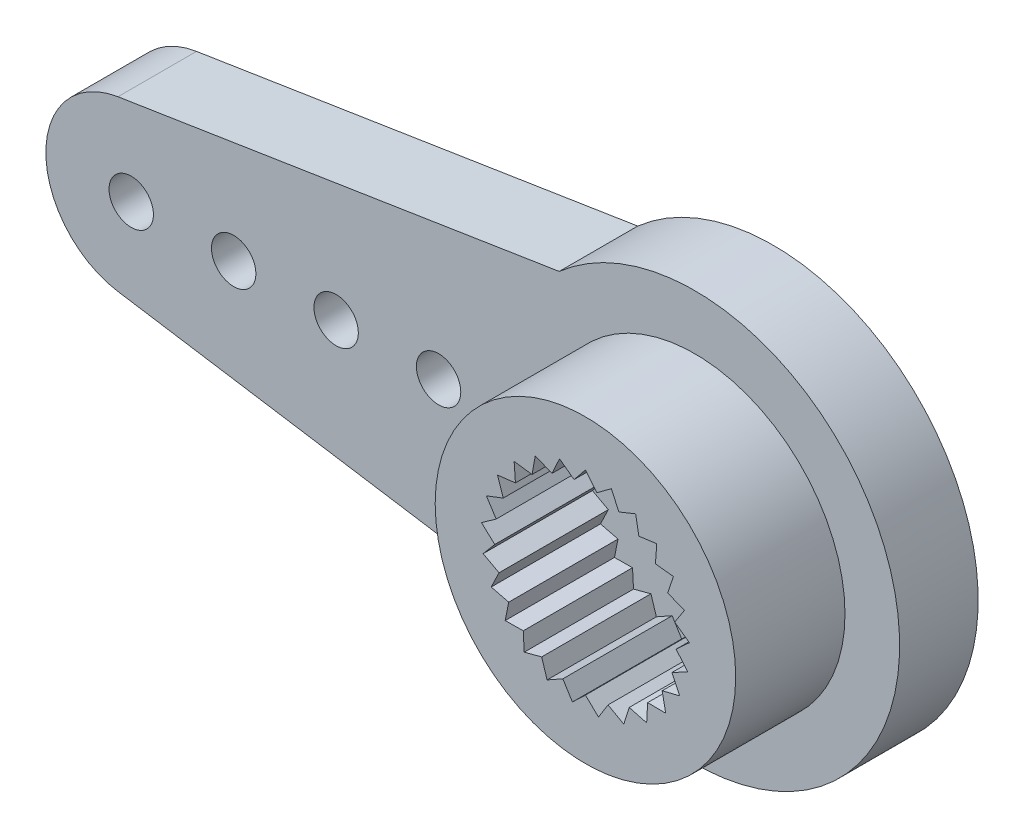
SolidWorks part; units mm, degrees
ref_plane "Front" through (0, 0, 0) normal (0, 0, 1) x (1, 0, 0)
ref_plane "Top" through (0, 0, 0) normal (0, 1, 0) x (1, 0, 0)
ref_plane "Right" through (0, 0, 0) normal (1, 0, 0) x (0, 0, -1)
sketch "Эскиз1" plane through (0, 0, 0) normal (0, 0, 1) x (1, 0, 0)
  line L0 (-3.9686, 4.5) -> (-16.8881, 2.4697)
  line L1 (-19, 4.5) -> (19, 4.5) construction
  line L2 (-19, 4.5) -> (-19, -4.5) construction
  line L3 (-19, -4.5) -> (19, -4.5) construction
  line L4 (19, 4.5) -> (19, -4.5) construction
  line L5 (0, -4.5) -> (0, 4.5) construction
  line L6 (-19, 0) -> (19, 0) construction
  line L7 (-3.9686, -4.5) -> (-16.8881, -2.4697)
  line L8 (3.9686, -4.5) -> (16.8881, -2.4697)
  line L9 (3.9686, 4.5) -> (16.8881, 2.4697)
  circle A0 centre (0, 0) radius 6 construction
  circle A1 centre (-16.5, 0) radius 2.5 construction
  arc A2 (-16.8881, 2.4697) -> (-16.8881, -2.4697) centre (-16.5, 0) ccw
  arc A3 (-3.9686, 4.5) -> (3.9686, 4.5) centre (0, 0) cw
  arc A4 (-3.9686, -4.5) -> (3.9686, -4.5) centre (0, 0) ccw
  circle A5 centre (16.5, 0) radius 2.5 construction
  arc A6 (16.8881, 2.4697) -> (16.8881, -2.4697) centre (16.5, 0) cw
  circle A7 centre (-16.5, 0) radius 0.65
  circle A8 centre (-13.5, 0) radius 0.65
  circle A9 centre (-10.5, 0) radius 0.65
  circle A10 centre (-7.5, 0) radius 0.65
  circle A11 centre (16.5, 0) radius 0.65
  circle A12 centre (7.5, 0) radius 0.65
  circle A13 centre (10.5, 0) radius 0.65
  circle A14 centre (13.5, 0) radius 0.65
  circle A15 centre (0, 0) radius 1.5
  dimension "D1" = 12
  dimension "D4" = 5
  dimension "D5" = 1.3
  dimension "D7" = 3
  dimension "D2" = 9
  dimension "D3" = 38
  dimension "D6" = 4
extrude "Бобышка-Вытянуть1" add sketch "Эскиз1" along normal blind 2.3
sketch "Эскиз2" plane through (0, 0, 2.3) normal (0, 0, 1) x (1, 0, 0)
  line L0 (0, 0) -> (0, 3.05) construction
  line L1 (0, 0) -> (0.3823, 3.0259) construction
  line L2 (0.3334, 2.6394) -> (0, 3.05)
  line L3 (-0.3334, 2.6394) -> (0, 3.05)
  line L4 (0.3334, 2.6394) -> (0.7585, 2.9542)
  line L5 (0.9794, 2.4736) -> (0.7585, 2.9542)
  line L6 (0.9794, 2.4736) -> (1.4693, 2.6727)
  line L7 (1.5638, 2.1523) -> (1.4693, 2.6727)
  line L8 (1.5638, 2.1523) -> (2.0879, 2.2234)
  line L9 (2.0499, 1.6958) -> (2.0879, 2.2234)
  line L10 (2.0499, 1.6958) -> (2.5752, 1.6343)
  line L11 (2.4072, 1.1328) -> (2.5752, 1.6343)
  line L12 (2.4072, 1.1328) -> (2.9007, 0.9425)
  line L13 (2.6133, 0.4985) -> (2.9007, 0.9425)
  line L14 (2.6133, 0.4985) -> (3.044, 0.1915)
  line L15 (2.6552, -0.167) -> (3.044, 0.1915)
  line L16 (2.6552, -0.167) -> (2.996, -0.5715)
  line L17 (2.5302, -0.8221) -> (2.996, -0.5715)
  line L18 (2.5302, -0.8221) -> (2.7597, -1.2986)
  line L19 (2.2463, -1.4255) -> (2.7597, -1.2986)
  line L20 (2.2463, -1.4255) -> (2.3501, -1.9441)
  line L21 (1.8212, -1.9394) -> (2.3501, -1.9441)
  line L22 (1.8212, -1.9394) -> (1.7927, -2.4675)
  line L23 (1.2817, -2.3313) -> (1.7927, -2.4675)
  line L24 (1.2817, -2.3313) -> (1.1228, -2.8358)
  line L25 (0.6616, -2.5768) -> (1.1228, -2.8358)
  line L26 (0.6616, -2.5768) -> (0.3823, -3.0259)
  line L27 (0, -2.6604) -> (0.3823, -3.0259)
  line L28 (0, -2.6604) -> (-0.3823, -3.0259)
  line L29 (-0.6616, -2.5768) -> (-0.3823, -3.0259)
  line L30 (-0.6616, -2.5768) -> (-1.1228, -2.8358)
  line L31 (-1.2817, -2.3313) -> (-1.1228, -2.8358)
  line L32 (-1.2817, -2.3313) -> (-1.7927, -2.4675)
  line L33 (-1.8212, -1.9394) -> (-1.7927, -2.4675)
  line L34 (-1.8212, -1.9394) -> (-2.3501, -1.9441)
  line L35 (-2.2463, -1.4255) -> (-2.3501, -1.9441)
  line L36 (-2.2463, -1.4255) -> (-2.7597, -1.2986)
  line L37 (-2.5302, -0.8221) -> (-2.7597, -1.2986)
  line L38 (-2.5302, -0.8221) -> (-2.996, -0.5715)
  line L39 (-2.6552, -0.167) -> (-2.996, -0.5715)
  line L40 (-2.6552, -0.167) -> (-3.044, 0.1915)
  line L41 (-2.6133, 0.4985) -> (-3.044, 0.1915)
  line L42 (-2.6133, 0.4985) -> (-2.9007, 0.9425)
  line L43 (-2.4072, 1.1328) -> (-2.9007, 0.9425)
  line L44 (-2.4072, 1.1328) -> (-2.5752, 1.6343)
  line L45 (-2.0499, 1.6958) -> (-2.5752, 1.6343)
  line L46 (-2.0499, 1.6958) -> (-2.0879, 2.2234)
  line L47 (-1.5638, 2.1523) -> (-2.0879, 2.2234)
  line L48 (-1.5638, 2.1523) -> (-1.4693, 2.6727)
  line L49 (-0.9794, 2.4736) -> (-1.4693, 2.6727)
  line L50 (-0.9794, 2.4736) -> (-0.7585, 2.9542)
  line L51 (-0.3334, 2.6394) -> (-0.7585, 2.9542)
  circle A0 centre (0, 0) radius 4.4
  circle A1 centre (0, 0) radius 3.05 construction
  circle A2 centre (0, 0) radius 2.65 construction
  point P83 (0, 0)
  dimension "D1" = 8.8
  dimension "D2" = 6.1
  dimension "D3" = 5.3
  dimension "D5" = 25
  dimension "D4" = 7.2
extrude "Бобышка-Вытянуть2" add sketch "Эскиз2" along normal blind 3.2
sketch "Эскиз3" plane through (0, 0, 0) normal (0, 0, -1) x (-1, 0, 0)
  circle A0 centre (0, 0) radius 4.4
  circle A1 centre (0, 0) radius 3.4
  circle A2 centre (0, 0) radius 2.75
  circle M17 centre (0, 0) radius 1.5
  dimension "D1" = 8.8
  dimension "D2" = 6.8
  dimension "D3" = 5.5
extrude "Вырез-Вытянуть1" cut sketch "Эскиз3" against normal blind 1 contours A0 A1 | A2 M17
sketch "Sketch1" plane through (0, 0, 0) normal (0, 0, -1) x (-1, 0, 0)
  line L4 (-3.9686, 4.5) -> (-16.8881, 2.4697)
  line L5 (-16.8881, -2.4697) -> (-3.9686, -4.5)
  line L6 (3.9686, -4.5) -> (16.8881, -2.4697)
  line L7 (16.8881, 2.4697) -> (3.9686, 4.5)
  line L8 (-3.9686, 4.5) -> (-16.8881, 2.4697)
  line L9 (-16.8881, -2.4697) -> (-3.9686, -4.5)
  arc A0 (-3.9686, 4.5) -> (-3.9686, -4.5) centre (0, 0) ccw
  arc A5 (3.9686, 4.5) -> (-3.9686, 4.5) centre (0, 0) ccw
  arc A6 (-16.8881, 2.4697) -> (-16.8881, -2.4697) centre (-16.5, 0) ccw
  arc A7 (-3.9686, -4.5) -> (3.9686, -4.5) centre (0, 0) ccw
  arc A8 (16.8881, -2.4697) -> (16.8881, 2.4697) centre (16.5, 0) ccw
  arc A10 (-16.8881, 2.4697) -> (-16.8881, -2.4697) centre (-16.5, 0) ccw
  dimension "D1" = 0
extrude "Cut-Extrude1" cut sketch "Sketch1" against normal up to next
